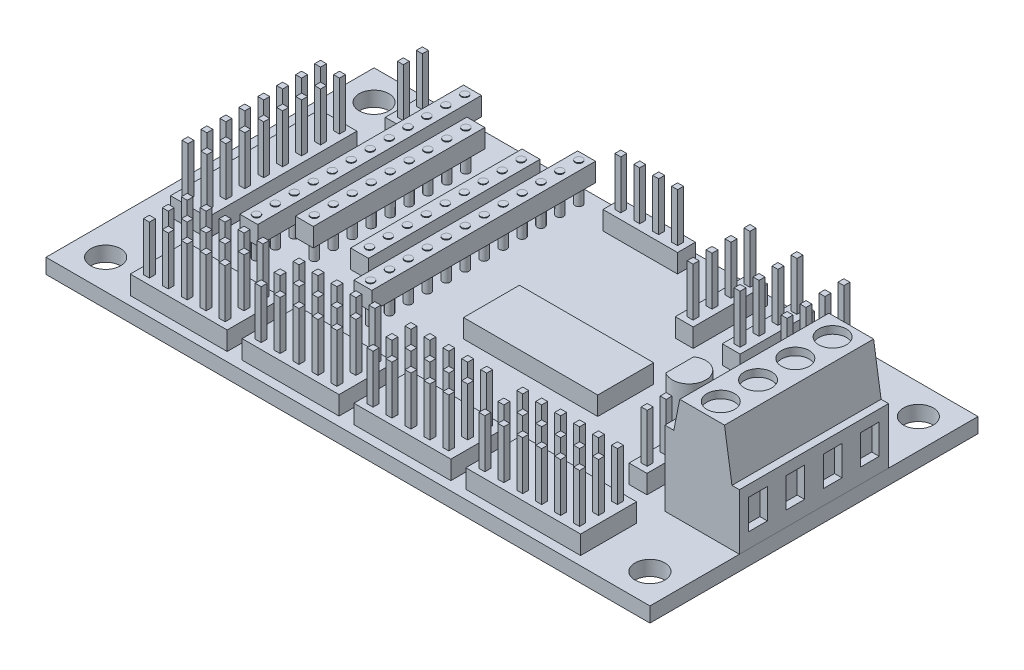
SolidWorks part; units mm, degrees
ref_plane "Front" through (0, 0, 0) normal (0, 0, 1) x (1, 0, 0)
ref_plane "Top" through (0, 0, 0) normal (0, 1, 0) x (1, 0, 0)
ref_plane "Right" through (0, 0, 0) normal (1, 0, 0) x (0, 0, -1)
sketch "Esquisse1" plane through (0, 0, 0) normal (0, 1, 0) x (1, 0, 0)
  line L1 (-40.5, -22) -> (40.5, -22)
  line L2 (-40.5, -22) -> (-40.5, 22)
  line L3 (-40.5, 22) -> (40.5, 22)
  line L4 (40.5, -22) -> (40.5, 22)
  line L5 (0, 22) -> (0, -22) construction
  line L6 (-40.5, 0) -> (40.5, 0) construction
  circle A0 centre (-36.5, 18) radius 2
  circle A1 centre (36.5, 18) radius 2
  circle A2 centre (-36.5, -18) radius 2
  circle A3 centre (36.5, -18) radius 2
  point P0 (0, 0)
  dimension "D3" = 73
  dimension "D4" = 36
  dimension "D5" = 4
  dimension "D6" = 81.3941
  dimension "D7" = 4
  dimension "D8" = 4
  dimension "D1" = 44
  dimension "D2" = 81
extrude "Boss.-Extru.1" add sketch "Esquisse1" along normal blind 2
sketch "Esquisse3" plane through (0, 0, 0) normal (0, 0, 1) x (1, 0, 0)
  line L0 (30.5, 2) -> (30.5, 12)
  line L1 (-40.5, 2) -> (40.5, 2) construction
  line L2 (30.5, 12) -> (31.7, 12)
  line L3 (31.7, 12) -> (32.5, 16)
  line L4 (32.5, 16) -> (38.5, 16)
  line L5 (38.5, 16) -> (39.5, 9.5)
  line L6 (39.5, 9.5) -> (40.5, 9.5)
  line L7 (40.5, 9.5) -> (40.5, 2)
  line L8 (40.5, 2) -> (30.5, 2)
  dimension "D1" = 10
  dimension "D2" = 7.5
  dimension "D3" = 10
  dimension "D4" = 14
  dimension "D5" = 6
  dimension "D6" = 1
  dimension "D7" = 1.2
  dimension "D8" = 2
extrude "Boss.-Extru.3" add sketch "Esquisse3" along normal mid plane 20 separate body
sketch "Esquisse5" plane through (0, 16, 0) normal (0, 1, 0) x (1, 0, 0)
  line L0 (38.5, -10) -> (32.5, -10) construction
  line L2 (38.5, 10) -> (32.5, 10) construction
  circle A0 centre (35.5, -7.5) radius 1.85
  circle A1 centre (35.5, -2.5) radius 1.85
  circle A2 centre (35.5, 2.5) radius 1.85
  circle A3 centre (35.5, 7.5) radius 1.85
  point P10 (35.5, -10)
  dimension "D1" = 4
  dimension "D2" = 3.7
  dimension "D3" = 2.5
  dimension "D4" = 2.5
  dimension "D5" = 5
extrude "Enlèv. mat.-Extru.1" cut sketch "Esquisse5" against normal blind 1
sketch "Esquisse6" plane through (40.5, 0, 0) normal (1, 0, 0) x (0, 0, -1)
  line L0 (-3.75, 8) -> (-3.75, 4)
  line L1 (-8.75, 8) -> (-6.25, 8)
  line L2 (-8.75, 8) -> (-8.75, 4)
  line L3 (-8.75, 4) -> (-6.25, 4)
  line L4 (-6.25, 8) -> (-6.25, 4)
  line L5 (-3.75, 8) -> (-1.25, 8)
  line L6 (-1.25, 8) -> (-1.25, 4)
  line L7 (-3.75, 4) -> (-1.25, 4)
  line L8 (1.25, 8) -> (1.25, 4)
  line L9 (1.25, 8) -> (3.75, 8)
  line L10 (3.75, 8) -> (3.75, 4)
  line L11 (1.25, 4) -> (3.75, 4)
  line L12 (6.25, 8) -> (6.25, 4)
  line L13 (6.25, 8) -> (8.75, 8)
  line L14 (8.75, 8) -> (8.75, 4)
  line L15 (6.25, 4) -> (8.75, 4)
  line L16 (-10, 2) -> (-10, 9.5) construction
  line L17 (10, 2) -> (10, 9.5) construction
  line L18 (-10, 2) -> (10, 2) construction
  point P4 (-7.5, 8)
  point P19 (7.5, 8)
  dimension "D1" = 4
  dimension "D2" = 2.5
  dimension "D3" = 2.5
  dimension "D4" = 2.5
  dimension "D5" = 4
  dimension "D6" = 2
extrude "Enlèv. mat.-Extru.2" cut sketch "Esquisse6" against normal blind 1
sketch "Esquisse4" plane through (0, 2, 0) normal (0, 1, 0) x (1, 0, 0)
  line L0 (-27.5, 6) -> (-18.65, 6) construction
  line L1 (-36.8, 11) -> (-31.8, 11)
  line L2 (-36.8, 11) -> (-36.8, -9)
  line L3 (-36.8, -9) -> (-31.8, -9)
  line L4 (-31.8, 11) -> (-31.8, -9)
  line L5 (-31.5, 19.5) -> (-29.1, 19.5)
  line L6 (-31.5, 19.5) -> (-31.5, 14.5)
  line L7 (-31.5, 14.5) -> (-29.1, 14.5)
  line L8 (-29.1, 19.5) -> (-29.1, 14.5)
  line L9 (-27.5, 21) -> (-25.1, 21)
  line L10 (-27.5, 21) -> (-27.5, -9)
  line L11 (-27.5, -9) -> (-25.1, -9)
  line L12 (-25.1, 21) -> (-25.1, -9)
  line L13 (-23.55, 17.5) -> (-21.15, 17.5)
  line L14 (-23.55, 17.5) -> (-23.55, -5.5)
  line L15 (-23.55, -5.5) -> (-21.15, -5.5)
  line L16 (-21.15, 17.5) -> (-21.15, -5.5)
  line L17 (-6.2, 20.8) -> (3.8, 20.8)
  line L18 (-6.2, 20.8) -> (-6.2, 18.4)
  line L19 (-6.2, 18.4) -> (3.8, 18.4)
  line L20 (3.8, 20.8) -> (3.8, 18.4)
  line L21 (11.1, 20.8) -> (13.5, 20.8)
  line L22 (11.1, 20.8) -> (11.1, 10.8)
  line L23 (11.1, 10.8) -> (13.5, 10.8)
  line L24 (13.5, 20.8) -> (13.5, 10.8)
  line L25 (17.4, 20.8) -> (19.8, 20.8)
  line L26 (17.4, 20.8) -> (17.4, 10.8)
  line L27 (17.4, 10.8) -> (19.8, 10.8)
  line L28 (19.8, 20.8) -> (19.8, 10.8)
  line L29 (23.7, 20.8) -> (26.1, 20.8)
  line L30 (23.7, 20.8) -> (23.7, 10.8)
  line L31 (23.7, 10.8) -> (26.1, 10.8)
  line L32 (26.1, 20.8) -> (26.1, 10.8)
  line L33 (-30.4, -13.3) -> (-17.4, -13.3)
  line L34 (-30.4, -13.3) -> (-30.4, -20.8)
  line L35 (-30.4, -20.8) -> (-17.4, -20.8)
  line L36 (-17.4, -13.3) -> (-17.4, -20.8)
  line L37 (-15.4, -13.3) -> (-2.4, -13.3)
  line L38 (-15.4, -13.3) -> (-15.4, -20.8)
  line L39 (-15.4, -20.8) -> (-2.4, -20.8)
  line L40 (-2.4, -13.3) -> (-2.4, -20.8)
  line L41 (-0.4, -13.3) -> (12.6, -13.3)
  line L42 (-0.4, -13.3) -> (-0.4, -20.8)
  line L43 (-0.4, -20.8) -> (12.6, -20.8)
  line L44 (12.6, -13.3) -> (12.6, -20.8)
  line L45 (14.6, -13.3) -> (30, -13.3)
  line L46 (14.6, -13.3) -> (14.6, -20.8)
  line L47 (14.6, -20.8) -> (30, -20.8)
  line L48 (30, -13.3) -> (30, -20.8)
  line L49 (-3, 4) -> (15, 4)
  line L50 (-3, 4) -> (-3, -3.5)
  line L51 (-3, -3.5) -> (15, -3.5)
  line L52 (15, 4) -> (15, -3.5)
  line L53 (25, -4.3) -> (27.4, -4.3)
  line L54 (25, -4.3) -> (25, -9.3)
  line L55 (25, -9.3) -> (27.4, -9.3)
  line L56 (27.4, -4.3) -> (27.4, -9.3)
  line L57 (-18.65, 6) -> (-18.65, 21) construction
  line L58 (40.5, 22) -> (-40.5, 22) construction
  line L59 (40.5, -22) -> (40.5, 22) construction
  line L60 (-40.5, 22) -> (-40.5, -22) construction
  line L61 (-40.5, -22) -> (40.5, -22) construction
  line L62 (-13.75, 17.5) -> (-16.15, 17.5)
  line L63 (-13.75, 17.5) -> (-13.75, -5.5)
  line L64 (-13.75, -5.5) -> (-16.15, -5.5)
  line L65 (-16.15, 17.5) -> (-16.15, -5.5)
  line L66 (-9.8, 21) -> (-12.2, 21)
  line L67 (-9.8, 21) -> (-9.8, -9)
  line L68 (-9.8, -9) -> (-12.2, -9)
  line L69 (-12.2, 21) -> (-12.2, -9)
  point P58 (-21.15, 6)
  point P64 (3.8, 19.6)
  dimension "D1" = 1
  dimension "D2" = 23
  dimension "D3" = 1.2
  dimension "D4" = 2.4
  dimension "D5" = 1.2
  dimension "D6" = 15
  dimension "D7" = 10
  dimension "D8" = 14.4
  dimension "D9" = 3.9
  dimension "D10" = 3.9
  dimension "D11" = 30
  dimension "D12" = 7.3
  dimension "D13" = 10
  dimension "D14" = 7.5
  dimension "D15" = 18
  dimension "D16" = 2.5
  dimension "D17" = 9
  dimension "D18" = 5
  dimension "D19" = 20
  dimension "D20" = 13
  dimension "D21" = 11
  dimension "D22" = 3.7
  dimension "D23" = 5
  dimension "D24" = 5
  dimension "D25" = 15.5
  dimension "D26" = 17.7
  dimension "D27" = 17.7
  dimension "D28" = 5
  dimension "D29" = 13
  dimension "D30" = 43.5
  dimension "D31" = 26
  dimension "D32" = 10.1
  dimension "D33" = 10.5
  dimension "D34" = 13
  dimension "D35" = 15.4
  dimension "D36" = 1.2
  dimension "D37" = 7.5
  dimension "D38" = 2
  dimension "D39" = 2
  dimension "D40" = 2
extrude "Boss.-Extru.4" add sketch "Esquisse4" along normal blind 2.5 separate body
move or copy body "Corps-Déplacer/Copier1" bodies to move or copy 119 118 107 106 copy no translate (0, 2.5, 0)
sketch "Esquisse7" plane through (0, 7, 0) normal (0, 1, 0) x (1, 0, 0)
  line L0 (-27.5, -9) -> (-25.1, -9) construction
  line L1 (-23.55, -5.5) -> (-21.15, -5.5) construction
  line L4 (-27.5, 6) -> (-18.65, 6) construction
  line L5 (-18.65, 6) -> (-18.65, 21) construction
  line L6 (-18.65, 6) -> (-18.65, 21) construction
  circle A0 centre (-26.3, -7.97) radius 0.5
  circle A1 centre (-22.35, -4.16) radius 0.5
  circle A2 centre (-26.3, -5.43) radius 0.5
  circle A3 centre (-26.3, -2.89) radius 0.5
  circle A4 centre (-26.3, -0.35) radius 0.5
  circle A5 centre (-22.35, -1.62) radius 0.5
  circle A6 centre (-22.35, 0.92) radius 0.5
  circle A7 centre (-22.35, 3.46) radius 0.5
  circle A8 centre (-26.3, 2.19) radius 0.5
  circle A9 centre (-26.3, 4.73) radius 0.5
  circle A10 centre (-26.3, 7.27) radius 0.5
  circle A11 centre (-26.3, 9.81) radius 0.5
  circle A12 centre (-26.3, 12.35) radius 0.5
  circle A13 centre (-26.3, 14.89) radius 0.5
  circle A14 centre (-26.3, 17.43) radius 0.5
  circle A15 centre (-26.3, 19.97) radius 0.5
  circle A16 centre (-22.35, 6) radius 0.5
  circle A17 centre (-22.35, 8.54) radius 0.5
  circle A18 centre (-22.35, 11.08) radius 0.5
  circle A19 centre (-22.35, 13.62) radius 0.5
  circle A20 centre (-22.35, 16.16) radius 0.5
  circle A21 centre (-11, -7.97) radius 0.5
  circle A22 centre (-14.95, -4.16) radius 0.5
  circle A23 centre (-11, -5.43) radius 0.5
  circle A24 centre (-11, -2.89) radius 0.5
  circle A25 centre (-11, -0.35) radius 0.5
  circle A26 centre (-11, 2.19) radius 0.5
  circle A27 centre (-11, 4.73) radius 0.5
  circle A28 centre (-11, 7.27) radius 0.5
  circle A29 centre (-11, 9.81) radius 0.5
  circle A30 centre (-11, 12.35) radius 0.5
  circle A31 centre (-11, 14.89) radius 0.5
  circle A32 centre (-11, 17.43) radius 0.5
  circle A33 centre (-11, 19.97) radius 0.5
  circle A34 centre (-14.95, -1.62) radius 0.5
  circle A35 centre (-14.95, 0.92) radius 0.5
  circle A36 centre (-14.95, 3.46) radius 0.5
  circle A37 centre (-14.95, 6) radius 0.5
  circle A38 centre (-14.95, 8.54) radius 0.5
  circle A39 centre (-14.95, 11.08) radius 0.5
  circle A40 centre (-14.95, 13.62) radius 0.5
  circle A41 centre (-14.95, 16.16) radius 0.5
  point P6 (-26.3, -9)
  point P9 (-22.35, -5.5)
  dimension "D1" = 1
  dimension "D4" = 2.54
  dimension "D5" = 2.54
  dimension "D6" = 1.27
  dimension "D2" = 12
  dimension "D3" = 9
extrude "Boss.-Extru.5" add sketch "Esquisse7" against normal blind 8 from offset 0.1 separate body
sketch "Esquisse8" plane through (0, 2, 0) normal (0, 1, 0) x (1, 0, 0)
  line L0 (22.5, 1.8708) -> (22.5, -1.8708)
  line L1 (30.5, -10) -> (30.5, 10) construction
  line L2 (-40.5, -22) -> (40.5, -22) construction
  arc A0 (22.5, -1.8708) -> (22.5, 1.8708) centre (23.75, 0) ccw
  point P1 (26, 0)
  dimension "D1" = 2.25
  dimension "D4" = 22
  dimension "D2" = 3.5
  dimension "D3" = 8
extrude "Boss.-Extru.6" add sketch "Esquisse8" along normal blind 8 separate body
sketch "Esquisse9" plane through (0, 2, 0) normal (0, 1, 0) x (1, 0, 0)
  line L0 (19, 11.59) -> (19, 12.39)
  line L1 (11.9, 11.59) -> (12.7, 11.59)
  line L2 (11.9, 11.59) -> (11.9, 12.39)
  line L3 (11.9, 12.39) -> (12.7, 12.39)
  line L4 (12.7, 11.59) -> (12.7, 12.39)
  line L5 (12.3, 12.39) -> (12.3, 11.59) construction
  line L6 (11.9, 11.99) -> (12.7, 11.99) construction
  line L7 (-30.7, 17.87) -> (-29.9, 17.87)
  line L8 (-30.7, 17.87) -> (-30.7, 18.67)
  line L9 (-30.7, 18.67) -> (-29.9, 18.67)
  line L10 (-29.9, 17.87) -> (-29.9, 18.67)
  line L11 (-30.3, 18.67) -> (-30.3, 17.87) construction
  line L12 (-30.7, 18.27) -> (-29.9, 18.27) construction
  line L13 (-35.97, 9.49) -> (-35.17, 9.49)
  line L14 (-35.97, 9.49) -> (-35.97, 10.29)
  line L15 (-35.97, 10.29) -> (-35.17, 10.29)
  line L16 (-35.17, 9.49) -> (-35.17, 10.29)
  line L17 (-35.57, 10.29) -> (-35.57, 9.49) construction
  line L18 (-35.97, 9.89) -> (-35.17, 9.89) construction
  line L19 (25.8, -5.93) -> (26.6, -5.93)
  line L20 (25.8, -5.93) -> (25.8, -5.13)
  line L21 (25.8, -5.13) -> (26.6, -5.13)
  line L22 (26.6, -5.93) -> (26.6, -5.13)
  line L23 (26.2, -5.13) -> (26.2, -5.93) construction
  line L24 (25.8, -5.53) -> (26.6, -5.53) construction
  line L25 (15.55, -19.99) -> (16.35, -19.99)
  line L26 (15.55, -19.99) -> (15.55, -19.19)
  line L27 (15.55, -19.19) -> (16.35, -19.19)
  line L28 (16.35, -19.99) -> (16.35, -19.19)
  line L29 (15.95, -19.19) -> (15.95, -19.99) construction
  line L30 (15.55, -19.59) -> (16.35, -19.59) construction
  line L31 (-5.41, 19.2) -> (-4.61, 19.2)
  line L32 (-5.41, 19.2) -> (-5.41, 20)
  line L33 (-5.41, 20) -> (-4.61, 20)
  line L34 (-4.61, 19.2) -> (-4.61, 20)
  line L35 (-5.01, 20) -> (-5.01, 19.2) construction
  line L36 (-5.41, 19.6) -> (-4.61, 19.6) construction
  line L37 (18.2, 12.39) -> (19, 12.39)
  line L38 (18.2, 11.59) -> (18.2, 12.39)
  line L39 (18.2, 11.59) -> (19, 11.59)
  line L40 (25.3, 11.59) -> (25.3, 12.39)
  line L41 (24.5, 12.39) -> (25.3, 12.39)
  line L42 (24.5, 11.59) -> (24.5, 12.39)
  line L43 (24.5, 11.59) -> (25.3, 11.59)
  line L44 (19, 14.13) -> (19, 14.93)
  line L45 (18.2, 14.93) -> (19, 14.93)
  line L46 (18.2, 14.13) -> (18.2, 14.93)
  line L47 (18.2, 14.13) -> (19, 14.13)
  line L48 (25.3, 14.13) -> (25.3, 14.93)
  line L49 (24.5, 14.93) -> (25.3, 14.93)
  line L50 (24.5, 14.13) -> (24.5, 14.93)
  line L51 (24.5, 14.13) -> (25.3, 14.13)
  line L52 (19, 16.67) -> (19, 17.47)
  line L53 (18.2, 17.47) -> (19, 17.47)
  line L54 (18.2, 16.67) -> (18.2, 17.47)
  line L55 (18.2, 16.67) -> (19, 16.67)
  line L56 (25.3, 16.67) -> (25.3, 17.47)
  line L57 (24.5, 17.47) -> (25.3, 17.47)
  line L58 (24.5, 16.67) -> (24.5, 17.47)
  line L59 (24.5, 16.67) -> (25.3, 16.67)
  line L60 (19, 19.21) -> (19, 20.01)
  line L61 (18.2, 20.01) -> (19, 20.01)
  line L62 (18.2, 19.21) -> (18.2, 20.01)
  line L63 (18.2, 19.21) -> (19, 19.21)
  line L64 (25.3, 19.21) -> (25.3, 20.01)
  line L65 (24.5, 20.01) -> (25.3, 20.01)
  line L66 (24.5, 19.21) -> (24.5, 20.01)
  line L67 (24.5, 19.21) -> (25.3, 19.21)
  line L68 (12.7, 14.13) -> (12.7, 14.93)
  line L69 (11.9, 14.93) -> (12.7, 14.93)
  line L70 (11.9, 14.13) -> (11.9, 14.93)
  line L71 (11.9, 14.13) -> (12.7, 14.13)
  line L72 (12.7, 16.67) -> (12.7, 17.47)
  line L73 (11.9, 17.47) -> (12.7, 17.47)
  line L74 (11.9, 16.67) -> (11.9, 17.47)
  line L75 (11.9, 16.67) -> (12.7, 16.67)
  line L76 (12.7, 19.21) -> (12.7, 20.01)
  line L77 (11.9, 20.01) -> (12.7, 20.01)
  line L78 (11.9, 19.21) -> (11.9, 20.01)
  line L79 (11.9, 19.21) -> (12.7, 19.21)
  line L80 (12.7, 11.59) -> (19, 11.59) construction
  line L81 (12.7, 11.59) -> (12.7, 14.13) construction
  line L82 (11.1, 10.8) -> (13.5, 10.8) construction
  line L83 (11.1, 20.8) -> (11.1, 10.8) construction
  line L84 (17.4, 10.8) -> (19.8, 10.8) construction
  line L85 (-6.2, 20.8) -> (-6.2, 18.4) construction
  line L86 (-31.5, 19.5) -> (-29.1, 19.5) construction
  line L87 (25, -4.3) -> (27.4, -4.3) construction
  line L88 (25, -6.8) -> (27.4, -6.8) construction
  line L89 (27.4, -4.3) -> (27.4, -9.3) construction
  line L90 (25, -4.3) -> (25, -9.3) construction
  line L91 (25.8, -7.67) -> (25.8, -8.47)
  line L92 (25.8, -8.47) -> (26.6, -8.47)
  line L93 (26.6, -7.67) -> (26.6, -8.47)
  line L94 (25.8, -7.67) -> (26.6, -7.67)
  line L95 (-31.5, 17) -> (-29.1, 17) construction
  line L96 (-29.1, 19.5) -> (-29.1, 14.5) construction
  line L97 (-31.5, 19.5) -> (-31.5, 14.5) construction
  line L98 (-30.7, 16.13) -> (-30.7, 15.33)
  line L99 (-30.7, 15.33) -> (-29.9, 15.33)
  line L100 (-29.9, 16.13) -> (-29.9, 15.33)
  line L101 (-30.7, 16.13) -> (-29.9, 16.13)
  line L102 (-36.8, 11) -> (-31.8, 11) construction
  line L103 (-33.43, 10.29) -> (-32.63, 10.29)
  line L104 (-32.63, 9.49) -> (-32.63, 10.29)
  line L105 (-33.43, 9.49) -> (-32.63, 9.49)
  line L106 (-33.43, 9.49) -> (-33.43, 10.29)
  line L107 (-33.43, 7.75) -> (-32.63, 7.75)
  line L108 (-32.63, 6.95) -> (-32.63, 7.75)
  line L109 (-33.43, 6.95) -> (-32.63, 6.95)
  line L110 (-33.43, 6.95) -> (-33.43, 7.75)
  line L111 (-33.43, 5.21) -> (-32.63, 5.21)
  line L112 (-32.63, 4.41) -> (-32.63, 5.21)
  line L113 (-33.43, 4.41) -> (-32.63, 4.41)
  line L114 (-33.43, 4.41) -> (-33.43, 5.21)
  line L115 (-33.43, 2.67) -> (-32.63, 2.67)
  line L116 (-32.63, 1.87) -> (-32.63, 2.67)
  line L117 (-33.43, 1.87) -> (-32.63, 1.87)
  line L118 (-33.43, 1.87) -> (-33.43, 2.67)
  line L119 (-33.43, 0.13) -> (-32.63, 0.13)
  line L120 (-32.63, -0.67) -> (-32.63, 0.13)
  line L121 (-33.43, -0.67) -> (-32.63, -0.67)
  line L122 (-33.43, -0.67) -> (-33.43, 0.13)
  line L123 (-33.43, -2.41) -> (-32.63, -2.41)
  line L124 (-32.63, -3.21) -> (-32.63, -2.41)
  line L125 (-33.43, -3.21) -> (-32.63, -3.21)
  line L126 (-33.43, -3.21) -> (-33.43, -2.41)
  line L127 (-33.43, -4.95) -> (-32.63, -4.95)
  line L128 (-32.63, -5.75) -> (-32.63, -4.95)
  line L129 (-33.43, -5.75) -> (-32.63, -5.75)
  line L130 (-33.43, -5.75) -> (-33.43, -4.95)
  line L131 (-33.43, -7.49) -> (-32.63, -7.49)
  line L132 (-32.63, -8.29) -> (-32.63, -7.49)
  line L133 (-33.43, -8.29) -> (-32.63, -8.29)
  line L134 (-33.43, -8.29) -> (-33.43, -7.49)
  line L135 (-35.97, 7.75) -> (-35.17, 7.75)
  line L136 (-35.17, 6.95) -> (-35.17, 7.75)
  line L137 (-35.97, 6.95) -> (-35.17, 6.95)
  line L138 (-35.97, 6.95) -> (-35.97, 7.75)
  line L139 (-35.97, 5.21) -> (-35.17, 5.21)
  line L140 (-35.17, 4.41) -> (-35.17, 5.21)
  line L141 (-35.97, 4.41) -> (-35.17, 4.41)
  line L142 (-35.97, 4.41) -> (-35.97, 5.21)
  line L143 (-35.97, 2.67) -> (-35.17, 2.67)
  line L144 (-35.17, 1.87) -> (-35.17, 2.67)
  line L145 (-35.97, 1.87) -> (-35.17, 1.87)
  line L146 (-35.97, 1.87) -> (-35.97, 2.67)
  line L147 (-35.97, 0.13) -> (-35.17, 0.13)
  line L148 (-35.17, -0.67) -> (-35.17, 0.13)
  line L149 (-35.97, -0.67) -> (-35.17, -0.67)
  line L150 (-35.97, -0.67) -> (-35.97, 0.13)
  line L151 (-35.97, -2.41) -> (-35.17, -2.41)
  line L152 (-35.17, -3.21) -> (-35.17, -2.41)
  line L153 (-35.97, -3.21) -> (-35.17, -3.21)
  line L154 (-35.97, -3.21) -> (-35.97, -2.41)
  line L155 (-35.97, -4.95) -> (-35.17, -4.95)
  line L156 (-35.17, -5.75) -> (-35.17, -4.95)
  line L157 (-35.97, -5.75) -> (-35.17, -5.75)
  line L158 (-35.97, -5.75) -> (-35.97, -4.95)
  line L159 (-35.97, -7.49) -> (-35.17, -7.49)
  line L160 (-35.17, -8.29) -> (-35.17, -7.49)
  line L161 (-35.97, -8.29) -> (-35.17, -8.29)
  line L162 (-35.97, -8.29) -> (-35.97, -7.49)
  line L163 (-35.97, 10.29) -> (-33.43, 10.29) construction
  line L164 (-35.97, 10.29) -> (-35.97, 7.75) construction
  line L165 (-36.8, 11) -> (-36.8, -9) construction
  line L166 (-2.87, 20) -> (-2.07, 20)
  line L167 (-2.07, 19.2) -> (-2.07, 20)
  line L168 (-2.87, 19.2) -> (-2.07, 19.2)
  line L169 (-2.87, 19.2) -> (-2.87, 20)
  line L170 (-0.33, 20) -> (0.47, 20)
  line L171 (0.47, 19.2) -> (0.47, 20)
  line L172 (-0.33, 19.2) -> (0.47, 19.2)
  line L173 (-0.33, 19.2) -> (-0.33, 20)
  line L174 (2.21, 20) -> (3.01, 20)
  line L175 (3.01, 19.2) -> (3.01, 20)
  line L176 (2.21, 19.2) -> (3.01, 19.2)
  line L177 (2.21, 19.2) -> (2.21, 20)
  line L178 (-5.41, 20) -> (-2.87, 20) construction
  line L179 (-6.2, 20.8) -> (3.8, 20.8) construction
  line L180 (18.09, -19.99) -> (18.89, -19.99)
  line L181 (18.89, -19.99) -> (18.89, -19.19)
  line L182 (18.09, -19.19) -> (18.89, -19.19)
  line L183 (18.09, -19.99) -> (18.09, -19.19)
  line L184 (20.63, -19.99) -> (21.43, -19.99)
  line L185 (21.43, -19.99) -> (21.43, -19.19)
  line L186 (20.63, -19.19) -> (21.43, -19.19)
  line L187 (20.63, -19.99) -> (20.63, -19.19)
  line L188 (23.17, -19.99) -> (23.97, -19.99)
  line L189 (23.97, -19.99) -> (23.97, -19.19)
  line L190 (23.17, -19.19) -> (23.97, -19.19)
  line L191 (23.17, -19.99) -> (23.17, -19.19)
  line L192 (25.71, -19.99) -> (26.51, -19.99)
  line L193 (26.51, -19.99) -> (26.51, -19.19)
  line L194 (25.71, -19.19) -> (26.51, -19.19)
  line L195 (25.71, -19.99) -> (25.71, -19.19)
  line L196 (28.25, -19.99) -> (29.05, -19.99)
  line L197 (29.05, -19.99) -> (29.05, -19.19)
  line L198 (28.25, -19.19) -> (29.05, -19.19)
  line L199 (28.25, -19.99) -> (28.25, -19.19)
  line L200 (18.09, -17.45) -> (18.89, -17.45)
  line L201 (18.89, -17.45) -> (18.89, -16.65)
  line L202 (18.09, -16.65) -> (18.89, -16.65)
  line L203 (18.09, -17.45) -> (18.09, -16.65)
  line L204 (20.63, -17.45) -> (21.43, -17.45)
  line L205 (21.43, -17.45) -> (21.43, -16.65)
  line L206 (20.63, -16.65) -> (21.43, -16.65)
  line L207 (20.63, -17.45) -> (20.63, -16.65)
  line L208 (23.17, -17.45) -> (23.97, -17.45)
  line L209 (23.97, -17.45) -> (23.97, -16.65)
  line L210 (23.17, -16.65) -> (23.97, -16.65)
  line L211 (23.17, -17.45) -> (23.17, -16.65)
  line L212 (25.71, -17.45) -> (26.51, -17.45)
  line L213 (26.51, -17.45) -> (26.51, -16.65)
  line L214 (25.71, -16.65) -> (26.51, -16.65)
  line L215 (25.71, -17.45) -> (25.71, -16.65)
  line L216 (28.25, -17.45) -> (29.05, -17.45)
  line L217 (29.05, -17.45) -> (29.05, -16.65)
  line L218 (28.25, -16.65) -> (29.05, -16.65)
  line L219 (28.25, -17.45) -> (28.25, -16.65)
  line L220 (18.09, -14.91) -> (18.89, -14.91)
  line L221 (18.89, -14.91) -> (18.89, -14.11)
  line L222 (18.09, -14.11) -> (18.89, -14.11)
  line L223 (18.09, -14.91) -> (18.09, -14.11)
  line L224 (20.63, -14.91) -> (21.43, -14.91)
  line L225 (21.43, -14.91) -> (21.43, -14.11)
  line L226 (20.63, -14.11) -> (21.43, -14.11)
  line L227 (20.63, -14.91) -> (20.63, -14.11)
  line L228 (23.17, -14.91) -> (23.97, -14.91)
  line L229 (23.97, -14.91) -> (23.97, -14.11)
  line L230 (23.17, -14.11) -> (23.97, -14.11)
  line L231 (23.17, -14.91) -> (23.17, -14.11)
  line L232 (25.71, -14.91) -> (26.51, -14.91)
  line L233 (26.51, -14.91) -> (26.51, -14.11)
  line L234 (25.71, -14.11) -> (26.51, -14.11)
  line L235 (25.71, -14.91) -> (25.71, -14.11)
  line L236 (28.25, -14.91) -> (29.05, -14.91)
  line L237 (29.05, -14.91) -> (29.05, -14.11)
  line L238 (28.25, -14.11) -> (29.05, -14.11)
  line L239 (28.25, -14.91) -> (28.25, -14.11)
  line L240 (15.55, -17.45) -> (16.35, -17.45)
  line L241 (16.35, -17.45) -> (16.35, -16.65)
  line L242 (15.55, -16.65) -> (16.35, -16.65)
  line L243 (15.55, -17.45) -> (15.55, -16.65)
  line L244 (15.55, -14.91) -> (16.35, -14.91)
  line L245 (16.35, -14.91) -> (16.35, -14.11)
  line L246 (15.55, -14.11) -> (16.35, -14.11)
  line L247 (15.55, -14.91) -> (15.55, -14.11)
  line L248 (15.55, -19.99) -> (18.09, -19.99) construction
  line L249 (15.55, -19.99) -> (15.55, -17.45) construction
  line L250 (14.6, -13.3) -> (14.6, -20.8) construction
  line L251 (14.6, -20.8) -> (30, -20.8) construction
  point P0 (12.3, 11.99)
  point P4 (-30.3, 18.27)
  point P11 (-35.57, 9.89)
  point P18 (26.2, -5.53)
  point P25 (15.95, -19.59)
  point P32 (-5.01, 19.6)
  point P103 (12.3, 10.8)
  point P107 (11.1, 15.8)
  point P108 (11.9, 14.53)
  point P111 (18.6, 10.8)
  point P112 (18.6, 11.59)
  point P115 (-6.2, 19.6)
  point P118 (-30.3, 19.5)
  point P121 (26.2, -4.3)
  point P133 (25.8, -8.07)
  point P147 (-34.3, 11)
  point P148 (-35.97, 2.27)
  point P212 (-36.8, 1)
  point P228 (-1.2, 20.8)
  point P229 (-2.47, 20)
  point P303 (14.6, -17.05)
  point P307 (22.3, -20.8)
  dimension "D1" = 0.8
  dimension "D2" = 3
  dimension "D3" = 4
  dimension "D4" = 90
  dimension "D5" = 6.3
  dimension "D6" = 2.54
  dimension "D7" = 1.27
  dimension "D8" = 2.54
  dimension "D9" = 2.54
  dimension "D10" = 1.27
  dimension "D13" = 90
  dimension "D14" = 2.54
  dimension "D15" = 2.54
  dimension "D16" = 1.27
  dimension "D18" = 2.54
  dimension "D19" = 1.27
  dimension "D20" = 6
  dimension "D22" = 90
  dimension "D23" = 2.54
  dimension "D24" = 2.54
  dimension "D25" = 2.54
  dimension "D26" = 6.35
  dimension "D11" = 2
  dimension "D12" = 8
  dimension "D17" = 4
  dimension "D21" = 3
extrude "Boss.-Extru.7" add sketch "Esquisse9" against normal blind 12 from offset 9 separate body
pattern_linear "Répétition linéaire1" count 4 spacing 15 along (-1, 0, 0) of bodies 173 206 207 208 209 214 213 212 211 221 219 218 217 216 222
